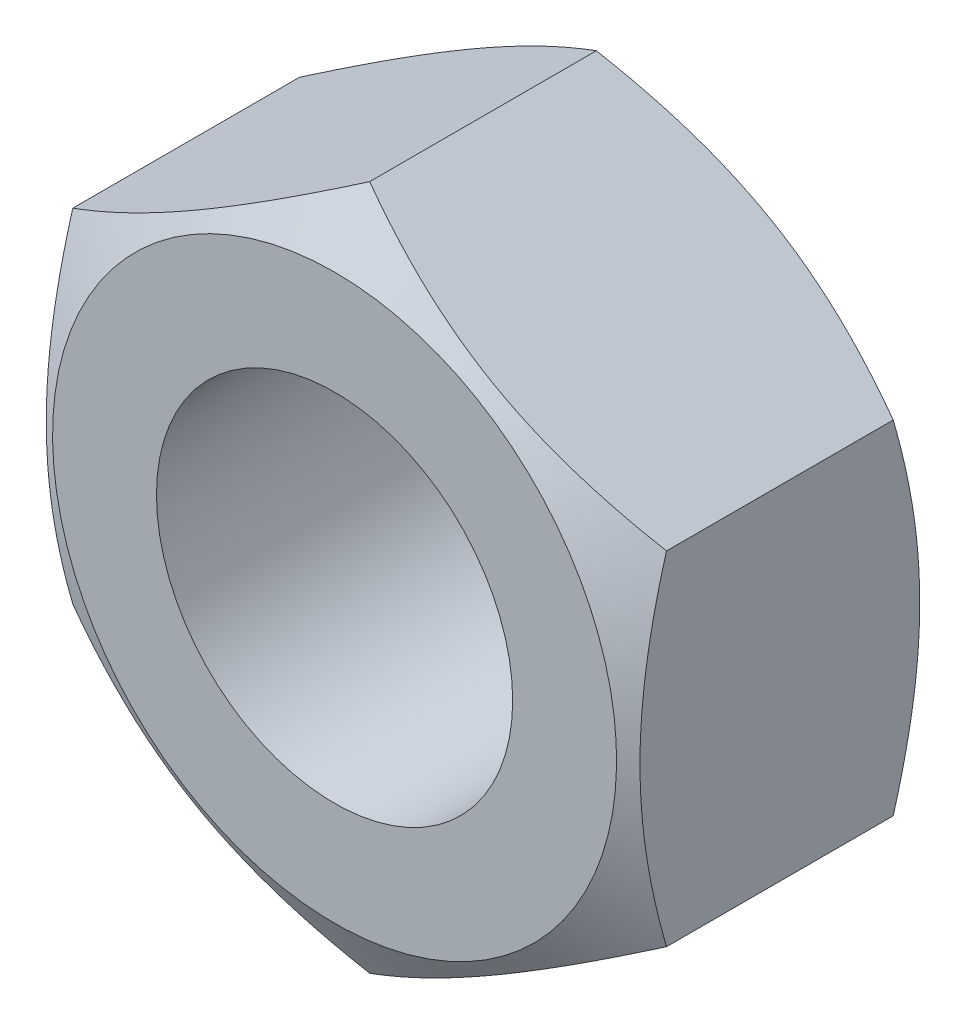
SolidWorks part; units mm, degrees
ref_plane "Спереди" through (0, 0, 0) normal (0, 0, 1) x (1, 0, 0)
ref_plane "Сверху" through (0, 0, 0) normal (0, 1, 0) x (1, 0, 0)
ref_plane "Справа" through (0, 0, 0) normal (1, 0, 0) x (0, 0, -1)
sketch "Эскиз1" plane through (0, 0, 0) normal (0, 0, 1) x (1, 0, 0)
  line L1 (0, 1.1547) -> (-1, 0.5774)
  line L2 (-1, 0.5774) -> (-1, -0.5774)
  line L3 (-1, -0.5774) -> (0, -1.1547)
  line L4 (0, -1.1547) -> (1, -0.5774)
  line L5 (1, -0.5774) -> (1, 0.5774)
  line L6 (1, 0.5774) -> (0, 1.1547)
  circle A0 centre (0, 0) radius 1 construction
  circle A1 centre (0, 0) radius 0.6
extrude "Бобышка-Вытянуть1" add sketch "Эскиз1" along normal blind 1
sketch "Эскиз2" plane through (0, 0, 0) normal (1, 0, 0) x (0, 0, -1)
  line L0 (0, 0) -> (0, 0.95)
  line L1 (0, 0.95) -> (-0.219, 1.3293)
  line L3 (0, 1.3293) -> (0, 0.95)
  line L4 (0, 0) -> (-1, 0)
  line L5 (-1, -0.5774) -> (-1, 0.5774) construction
  line L6 (-0.5, 0) -> (-0.5, -1.783)
  line L7 (0, 1.3293) -> (-0.219, 1.3293)
  line L8 (-1, 1.3293) -> (-0.781, 1.3293)
  line L9 (-1, 1.3293) -> (-1, 0.95)
  line L10 (-1, 0.95) -> (-0.781, 1.3293)
revolve "Вырез-Повернуть1" cut sketch "Эскиз2" angle 360 about L4
